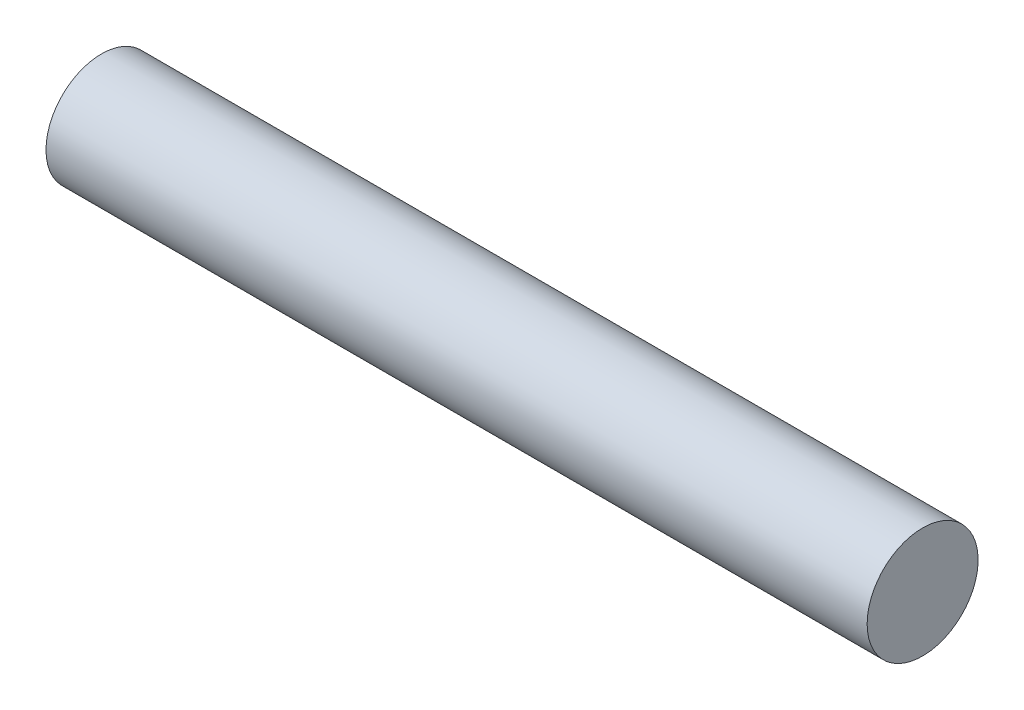
SolidWorks part; units mm, degrees
material "Copper"
ref_plane "Front Plane" through (0, 0, 0) normal (0, 0, 1) x (1, 0, 0)
ref_plane "Top Plane" through (0, 0, 0) normal (0, 1, 0) x (1, 0, 0)
ref_plane "Right Plane" through (0, 0, 0) normal (1, 0, 0) x (0, 0, -1)
sketch "Axial profile (mm)" plane through (0, 0, 0) normal (0, 0, 1) x (1, 0, 0)
  line L0 (-110, 0) -> (75, 0) construction
  line L1 (-140, 0) -> (-103, 0)
  line L2 (-103, 0) -> (-103, 2.5)
  line L3 (-103, 2.5) -> (-140, 2.5)
  line L4 (-140, 2.5) -> (-140, 0)
revolve "Full revolution" add sketch "Axial profile (mm)" angle 360 about L0
